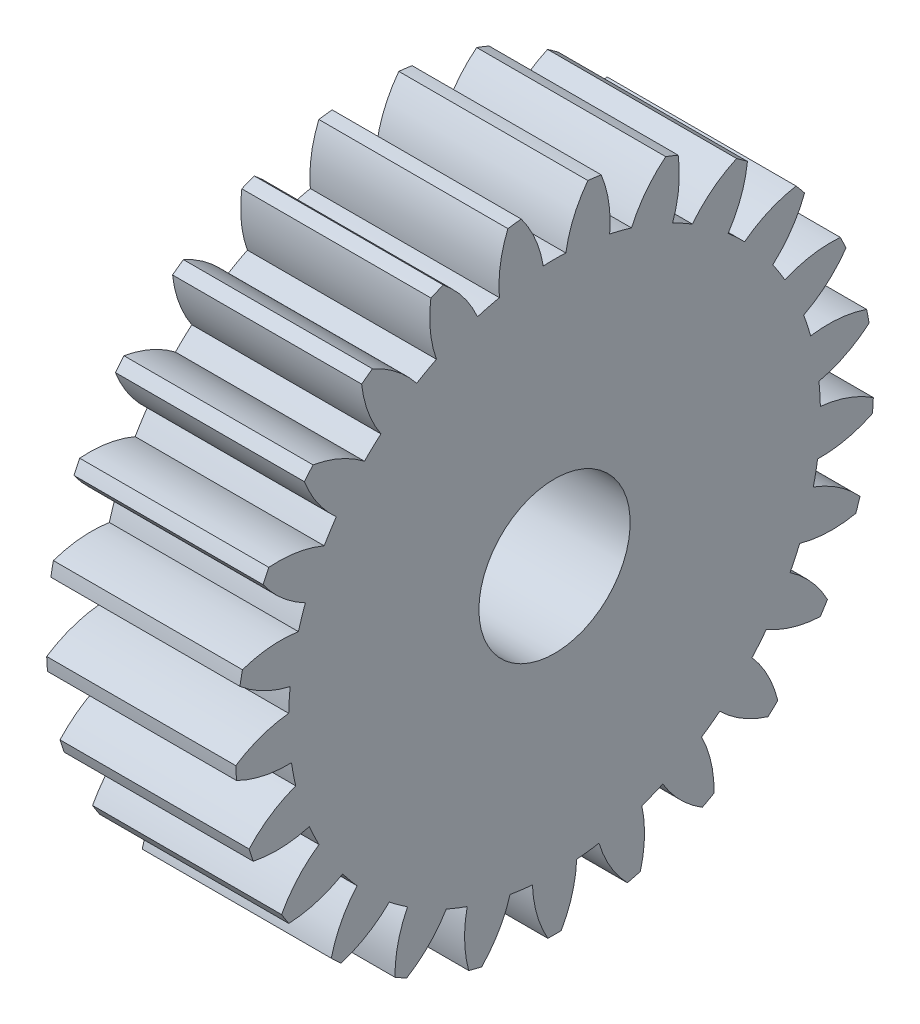
SolidWorks part; units mm, degrees
ref_plane "Plane1" through (0, 0, 0) normal (0, 0, 1) x (1, 0, 0)
ref_plane "Plane2" through (0, 0, 0) normal (0, 1, 0) x (1, 0, 0)
ref_plane "Plane3" through (0, 0, 0) normal (1, 0, 0) x (0, 0, -1)
sketch "HoldingSke" plane through (0, 0, 0) normal (0, 1, 0) x (1, 0, 0)
  line L0 (0, 0) -> (0.725, -0.3381)
  line L1 (-15, 0) -> (100, 0) construction
  line L2 (0, 0) -> (-2.1039, 2.3779)
  line L3 (0, 0) -> (-11.863, 4.5341)
  line L4 (0, 0) -> (7.8269, 3.6497)
  line L5 (0, 0) -> (-46.8476, -17.4728)
  line L6 (0, 0) -> (-8.2896, -5.593)
  line L7 (-2.1039, 2.3779) -> (8.6586, 51.2059)
  line L8 (-76.2, 54.61) -> (-74.8, 54.61)
  line L9 (-71.009, 38.7566) -> (-53.1078, 45.2721)
  line L10 (-76.2, 71.12) -> (104.1128, 71.12)
  line L11 (0, 0) -> (-10, 0)
  line L12 (-76.2, 101.6) -> (-76.155, 101.6)
  line L13 (24.9733, 27.94) -> (52.9518, 28.4284)
  line L14 (24.9733, 27.94) -> (24.9743, 27.94)
  line L15 (24.9733, 27.94) -> (100.4006, 29.5858)
  line L16 (-63.627, -1.25) -> (-12.827, -1.25)
  circle A0 centre (0, 0) radius 4
  circle A1 centre (0, 0) radius 14.0615
  circle A2 centre (0, 0) radius 37.5
  circle A3 centre (0, 0) radius 4
  dimension "Hub_dia" = 75
  dimension "Bore" = 8
  dimension "MBD" = 8
  dimension "Num_teeth" = 25
  dimension "Overall_len" = 50
  dimension "Show_teeth" = 25
  dimension "OAL" = 50.0001
  dimension "T_dim" = 1.4
  dimension "Ap" = 20
  dimension "H" = 19.05
  dimension "Pitch_radius" = 180.3128
  dimension "Addendum_fac" = 1
  dimension "Dedendum_fac" = 1.25
  dimension "Clearance_fac" = 0.25
  dimension "Dedendum_add" = 0.001
sketch "BasProSke" plane through (0, 0, 0) normal (0, 1, 0) x (1, 0, 0)
  line L0 (-10, 0) -> (60, 0) construction
  line L1 (0, 0) -> (0, 16.875)
  line L2 (0, 0) -> (10, 0)
  line L3 (10, 0) -> (10, 16.875)
  line L4 (10, 16.875) -> (0, 16.875)
revolve "Base-Revolve" add sketch "BasProSke" angle 360 about L0
sketch "TooCutSke" plane through (0, 0, 0) normal (1, 0, 0) x (0, 0, -1)
  line L1 (0, 0) -> (0, 107) construction
  line L2 (0, 0) -> (-1.0598, 15.589) construction
  line L3 (0, 0) -> (-3.9101, 30.9518) construction
  line L4 (-1.0598, 15.589) -> (-1.9551, 15.4759) construction
  arc A0 (0.5962, 14.0489) -> (-0.5962, 14.0489) centre (0, 0) ccw
  arc A1 (1.781, 16.8063) -> (-1.781, 16.8063) centre (0, 0) ccw
  circle A2 centre (0, 0) radius 15.625 construction
  circle A3 centre (0, 0) radius 14.6827 construction
  arc A4 (-0.5962, 14.0489) -> (-1.781, 16.8063) centre (-6.763, 13.0324) ccw
  arc A5 (1.781, 16.8063) -> (0.5962, 14.0489) centre (6.763, 13.0324) ccw
  dimension "Half_ang" = 7.2
extrude "ToothCut" cut sketch "TooCutSke" along normal through all
fillet "Breaks" [suppressed] radius 0.025
fillet "RootFillets" [suppressed] radius 0.3135
pattern_circular "TeethCuts" count 25 every 14.4 about axis through (-10, 0, 0) along (1, 0, 0) of "ToothCut", "RootFillets", "Breaks"
sketch "HubNeaOneSke" plane through (0, 0, 0) normal (-1, 0, 0) x (0, 0, 1)
  circle A0 centre (0, 0) radius 14.0615
extrude "HubNearOne" [suppressed] add sketch "HubNeaOneSke" along normal blind 40.0001
sketch "HubNeaBotSke" plane through (0, 0, 0) normal (-1, 0, 0) x (0, 0, 1)
  circle A0 centre (0, 0) radius 14.0615
extrude "HubNearBoth" [suppressed] add sketch "HubNeaBotSke" along normal blind 20
ref_plane "FarPln" through (10, 0, 0) normal (1, 0, 0) x (0, 0, -1)
sketch "HubFarSke" plane through (10, 0, 0) normal (1, 0, 0) x (0, 0, -1)
  circle A0 centre (0, 0) radius 14.0615
extrude "HubFar" [suppressed] add sketch "HubFarSke" along normal blind 20
sketch "BorSke" plane through (0, 0, 0) normal (1, 0, 0) x (0, 0, -1)
  circle A0 centre (0, 0) radius 4
  dimension "Diameter" = 8
extrude "Bore" cut sketch "BorSke" along normal mid plane 100.0001
sketch "KeySke" plane through (0, 0, 0) normal (1, 0, 0) x (0, 0, -1)
  line L0 (-1.5, 0) -> (-1.5, 5.4)
  line L1 (-1.5, 5.4) -> (1.5, 5.4)
  line L2 (1.5, 5.4) -> (1.5, 0)
  line L3 (0, 0) -> (0, 34) construction
  line L4 (-1.5, 0) -> (1.5, 0)
  dimension "Offset" = 5.4
  dimension "Width" = 3
extrude "Keyway" [suppressed] cut sketch "KeySke" along normal mid plane 100.0001
pattern_circular "Keyway2" [suppressed] count 2 every 90 about axis through (-10, 0, 0) along (1, 0, 0)
equation "' \"Module@HoldingSke\" = 6.35"
equation "' \"Num_teeth@HoldingSke\" = 12"
equation "' \"Ap@HoldingSke\" =  20"
equation "' \"Ap@HoldingSke\" = 20"
equation "' \"Width@HoldingSke\" = 0.5 * 25.4"
equation "' \"Hub_dia@HoldingSke\"= 1 * 25.4"
equation "' \"Hub_dia@HoldingSke\" = 1 * 25.4"
equation "' \"Overall_len@HoldingSke\" = 1.0 * 25.4"
equation "' \"Bore@HoldingSke\" = 0.75 * 25.4"
equation "' \"T_dim@HoldingSke\" = 0.1 * 25.4"
equation "' \"Width@KeySke\" = 0.25 * 25.4"
equation "' \"Show_teeth@HoldingSke\" = 13"
equation "' \"Backlash@HoldingSke\" = 0.009 * 25.4"
equation "' \"Addendum_fac@HoldingSke\" = 1.0"
equation "' \"Dedendum_fac@HoldingSke\" = 1.25"
equation "' \"Dedendum_add@HoldingSke\" = 0.00005 * 25.4"
equation "' \"Clearance_fac@HoldingSke\" = 0.25"
equation "\"Pitch@HoldingSke\" = 1 / \"Module@HoldingSke\""
equation "\"Overcut_dia@TooCutSke\" = (\"Num_teeth@HoldingSke\" + 2 * \"Addendum_fac@HoldingSke\") / \"Pitch@HoldingSke\" + 0.002 * 25.4"
equation "\"Pitch_dia@TooCutSke\" = \"Num_teeth@HoldingSke\" / \"Pitch@HoldingSke\""
equation "\"Base_dia@TooCutSke\" = \"Num_teeth@HoldingSke\" / \"Pitch@HoldingSke\" * cos((\"Ap@HoldingSke\"  * 3.14159265 / 180))"
equation "\"Root_dia@TooCutSke\" = (\"Num_teeth@HoldingSke\" + 2) / \"Pitch@HoldingSke\" - 2 * (\"Addendum_fac@HoldingSke\" + \"Dedendum_fac@HoldingSke\") / \"Pitch@HoldingSke\" - \"Dedendum_add@HoldingSke\" * 2"
equation "\"Half_ang@TooCutSke\" = 180 / \"Num_teeth@HoldingSke\""
equation "\"Half_CT@TooCutSke\" = \"Num_teeth@HoldingSke\" / \"Pitch@HoldingSke\" * sin((3.14159265 / 2 / \"Num_teeth@HoldingSke\")) / 2 - 7 * \"Backlash@HoldingSke\" / 4"
equation "\"Flank_rad@TooCutSke\" = \"Num_teeth@HoldingSke\" / \"Pitch@HoldingSke\" / 5"
equation "\"Radius@RootFillets\" = \"Clearance_fac@HoldingSke\" / \"Pitch@HoldingSke\" + \"Dedendum_add@HoldingSke\""
equation "\"Break_rad@Breaks\" = 0.02 / \"Pitch@HoldingSke\""
equation "\"Thickness@HoldingSke\" = \"Width@HoldingSke\""
equation "\"OAL@HoldingSke\" = \"Thickness@HoldingSke\""
equation "\"MHD@HoldingSke\" = (\"Num_teeth@HoldingSke\" + 2) / \"Pitch@HoldingSke\" - 2 * (\"Addendum_fac@HoldingSke\" + \"Dedendum_fac@HoldingSke\")  / \"Pitch@HoldingSke\" - \"Dedendum_add@HoldingSke\" * 2"
equation "\"MBD@HoldingSke\" = (\"Num_teeth@HoldingSke\" + 2) / \"Pitch@HoldingSke\" - 2 * (\"Addendum_fac@HoldingSke\" + \"Dedendum_fac@HoldingSke\")  / \"Pitch@HoldingSke\" - \"Dedendum_add@HoldingSke\" * 2 - 0.002 * 25.4"
equation "\"MHD@HoldingSke\" = ((sgn( \"MHD@HoldingSke\" - \"Hub_dia@HoldingSke\" )-1)*( \"MHD@HoldingSke\" - \"Hub_dia@HoldingSke\" ))/-2+ \"Hub_dia@HoldingSke\""
equation "\"MBD@HoldingSke\" = ((sgn( \"MBD@HoldingSke\" - \"Bore@HoldingSke\" )-1)*( \"MBD@HoldingSke\" - \"Bore@HoldingSke\" ))/-2+ \"Bore@HoldingSke\""
equation "\"OAL@HoldingSke\" = ((sgn( \"OAL@HoldingSke\" - \"Overall_len@HoldingSke\" )+1)*( \"OAL@HoldingSke\" - \"Overall_len@HoldingSke\" ))/2 + \"Overall_len@HoldingSke\" + 0.000002 * 25.4"
equation "\"Num_teeth@TeethCuts\" = int( \"Show_teeth@HoldingSke\" ) + 1"
equation "\"Num_teeth@TeethCuts\" = ((sgn( \"Num_teeth@TeethCuts\" - \"Num_teeth@HoldingSke\" )-1)*( \"Num_teeth@TeethCuts\" - \"Num_teeth@HoldingSke\" ))/-2+ \"Num_teeth@HoldingSke\""
equation "\"Num_teeth@TeethCuts\" = ((sgn( \"Num_teeth@TeethCuts\" - 2.0)+1)*( \"Num_teeth@TeethCuts\" - 2.0))/2 +2.0"
equation "\"Angle@TeethCuts\" = 360.0 / \"Num_teeth@HoldingSke\""
equation "\"Diameter@BasProSke\" = (\"Num_teeth@HoldingSke\" + 2 * \"Addendum_fac@HoldingSke\") / \"Pitch@HoldingSke\""
equation "\"Thickness@BasProSke\"  = \"Thickness@HoldingSke\""
equation "' \"Fillet_rad@BasProSke\" =  \"Thickness@HoldingSke\" * 0.05"
equation "' \"Fillet_rad@BasProSke\" = \"Thickness@HoldingSke\" * 0.05"
equation "\"MHD@HoldingSke\" = ((sgn( \"MHD@HoldingSke\" - \"Root_dia@TooCutSke\" )-1)*( \"MHD@HoldingSke\" - \"Root_dia@TooCutSke\" ))/-2+ \"Root_dia@TooCutSke\""
equation "\"Diameter@HubNeaOneSke\" = \"MHD@HoldingSke\""
equation "\"Length@HubNearOne\" = \"OAL@HoldingSke\" - \"Thickness@BasProSke\""
equation "\"Diameter@HubNeaBotSke\" = \"MHD@HoldingSke\""
equation "\"Length@HubNearBoth\" = ( \"OAL@HoldingSke\" - \"Thickness@BasProSke\" ) / 2.0"
equation "\"Thickness@FarPln\" = \"Thickness@BasProSke\""
equation "\"Diameter@HubFarSke\" = \"MHD@HoldingSke\""
equation "\"Length@HubFar\" = ( \"OAL@HoldingSke\" - \"Thickness@BasProSke\" ) / 2.0"
equation "\"Diameter@BorSke\" = \"MBD@HoldingSke\""
equation "\"D1@Bore\" = \"OAL@HoldingSke\" * 2.0"
equation "\"D1@Keyway\" = \"OAL@HoldingSke\" * 2.0"
equation "\"Offset@KeySke\" = \"T_dim@HoldingSke\" + \"MBD@HoldingSke\" / 2.0"
